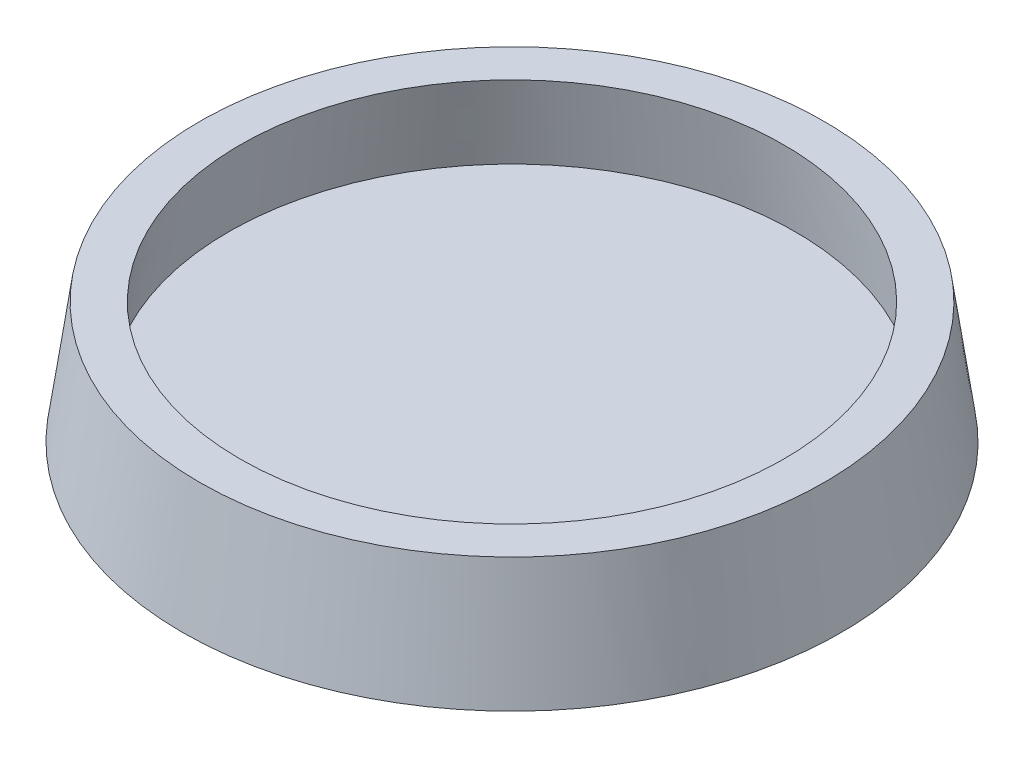
SolidWorks part; units mm, degrees
ref_plane "Alzado" through (0, 0, 0) normal (0, 0, 1) x (1, 0, 0)
ref_plane "Planta" through (0, 0, 0) normal (0, 1, 0) x (1, 0, 0)
ref_plane "Vista lateral" through (0, 0, 0) normal (1, 0, 0) x (0, 0, -1)
sketch "Croquis1" plane through (0, 0, 0) normal (1, 0, 0) x (0, 0, -1)
  line L0 (0, 0) -> (40.7027, 0)
  line L1 (40.7027, 0) -> (38.5946, 15)
  line L2 (38.5946, 15) -> (33.5946, 15)
  line L3 (33.5946, 15) -> (35, 5)
  line L4 (35, 5) -> (0, 5)
  line L5 (0, 5) -> (0, 0)
  dimension "D1" = 35
  dimension "D2" = 5
  dimension "D3" = 15
  dimension "D4" = 82
revolve "Revolución1" add sketch "Croquis1" angle 360 about L5
